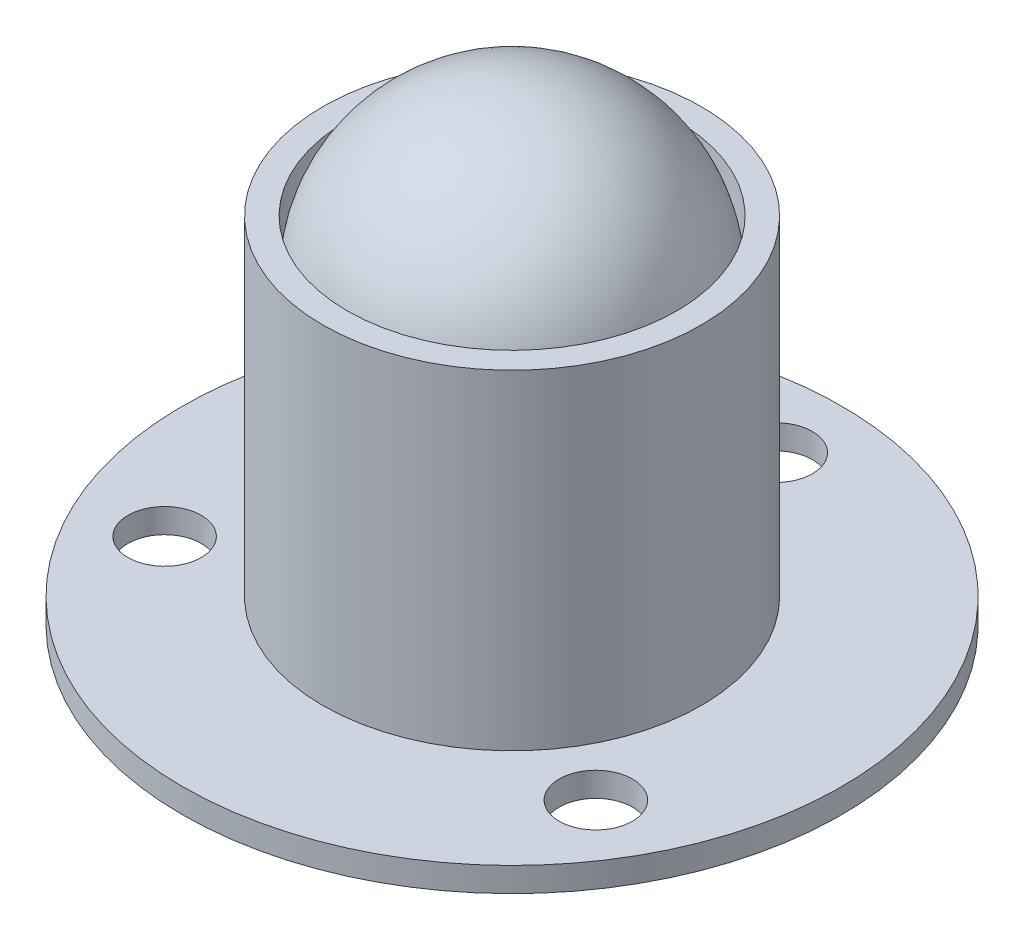
SolidWorks part; units mm, degrees
ref_plane "Front Plane" through (0, 0, 0) normal (0, 0, 1) x (1, 0, 0)
ref_plane "Top Plane" through (0, 0, 0) normal (0, 1, 0) x (1, 0, 0)
ref_plane "Right Plane" through (0, 0, 0) normal (1, 0, 0) x (0, 0, -1)
sketch "Sketch1" plane through (0, 0, 0) normal (0, 1, 0) x (1, 0, 0)
  circle A0 centre (0, 0) radius 13.5
  dimension "D1" = 27
extrude "Boss-Extrude1" add sketch "Sketch1" along normal blind 1
sketch "Sketch2" plane through (0, 1, 0) normal (0, 1, 0) x (1, 0, 0)
  circle A0 centre (0, 0) radius 7.75
  dimension "D1" = 15.5
extrude "Boss-Extrude2" add sketch "Sketch2" along normal blind 13.5
shell "Shell1" thickness 1
ref_plane "Plane1" through (0, 20, 0) normal (0, 1, 0) x (1, 0, 0)
ref_plane "Plane2" through (0, 12.25, 0) normal (0, 1, 0) x (1, 0, 0)
sketch "Sketch4" plane through (0, 12.25, 0) normal (0, 1, 0) x (1, 0, 0)
  line L0 (0, 6.75) -> (0, -6.75)
  arc A0 (0, 6.75) -> (0, -6.75) centre (0, 0) ccw
  circle A1 centre (0, 0) radius 6.75 construction
revolve "Revolve3" add sketch "Sketch4" angle 360 about L0
sketch "Sketch5" plane through (0, 1, 0) normal (0, 1, 0) x (1, 0, 0)
  line L0 (0, 0) -> (0.3012, 10.5) construction
  circle A0 centre (0.3012, 10.5) radius 1.5
  dimension "D1" = 3
  dimension "D2" = 10.5
extrude "Cut-Extrude1" cut sketch "Sketch5" against normal blind 13.5
pattern_circular "CirPattern1" count 3 over 360 about axis through (0, 0, 0) along (0, 1, 0) of "Cut-Extrude1"
